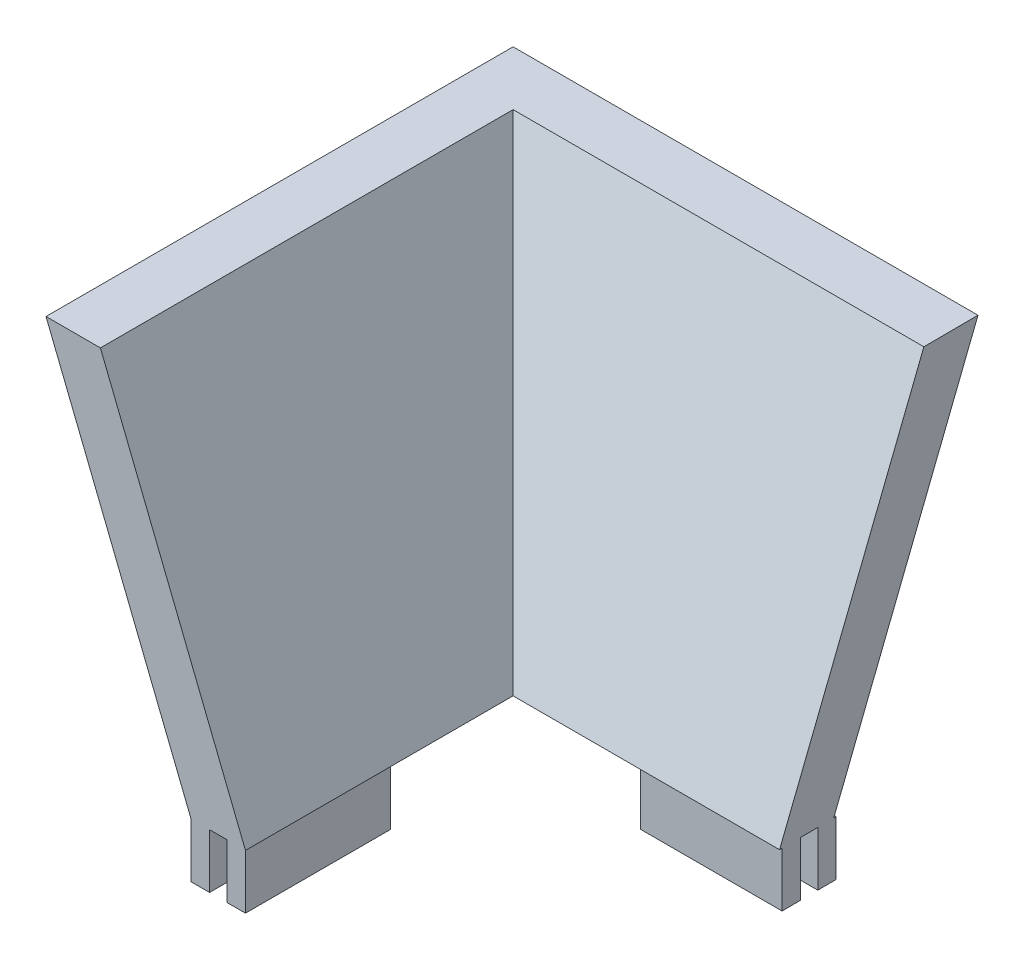
SolidWorks part; units mm, degrees
ref_plane "Front Plane" through (0, 0, 0) normal (0, 0, 1) x (1, 0, 0)
ref_plane "Top Plane" through (0, 0, 0) normal (0, 1, 0) x (1, 0, 0)
ref_plane "Right Plane" through (0, 0, 0) normal (1, 0, 0) x (0, 0, -1)
sketch "Sketch1" plane through (0, 0, 0) normal (0, 1, 0) x (1, 0, 0)
  line L1 (0, 0) -> (227.33, 0)
  line L2 (0, 0) -> (0, 225.552)
  line L3 (0, 225.552) -> (227.33, 225.552)
  line L4 (227.33, 0) -> (227.33, 225.552)
  dimension "D1" = 227.33
  dimension "D2" = 225.552
ref_plane "Plane1" through (0, 127, 0) normal (0, 1, 0) x (1, 0, 0)
sketch "Sketch2" plane through (0, 127, 0) normal (0, 1, 0) x (1, 0, 0)
  line L8 (-50.8, -50.8) -> (278.13, -50.8)
  line L9 (278.13, -50.8) -> (278.13, 276.352)
  line L10 (278.13, 276.352) -> (-50.8, 276.352)
  line L11 (-50.8, 276.352) -> (-50.8, -50.8)
  line L12 (-50.8, -50.8) -> (278.13, -50.8)
  line L13 (278.13, -50.8) -> (278.13, 276.352)
  line L14 (278.13, 276.352) -> (-50.8, 276.352)
  line L15 (-50.8, 276.352) -> (-50.8, -50.8)
  dimension "D1" = 50.8
loft "Loft1" add profiles "Sketch2" section "Sketch2" section "Sketch1"
sketch "Sketch3" plane through (0, 127, 0) normal (0, 1, 0) x (1, 0, 0)
  line L8 (-31.75, 257.302) -> (-31.75, -31.75)
  line L9 (-31.75, -31.75) -> (259.08, -31.75)
  line L10 (259.08, -31.75) -> (259.08, 257.302)
  line L11 (259.08, 257.302) -> (-31.75, 257.302)
  line L12 (-31.75, 257.302) -> (-31.75, -31.75)
  line L13 (-31.75, -31.75) -> (259.08, -31.75)
  line L14 (259.08, -31.75) -> (259.08, 257.302)
  line L15 (259.08, 257.302) -> (-31.75, 257.302)
  dimension "D1" = 19.05
sketch "Sketch4" plane through (0, 0, 0) normal (0, -1, 0) x (1, 0, 0)
  line L8 (208.28, -19.05) -> (19.05, -19.05)
  line L9 (19.05, -19.05) -> (19.05, -206.502)
  line L10 (19.05, -206.502) -> (208.28, -206.502)
  line L11 (208.28, -206.502) -> (208.28, -19.05)
  line L12 (208.28, -19.05) -> (19.05, -19.05)
  line L13 (19.05, -19.05) -> (19.05, -206.502)
  line L14 (19.05, -206.502) -> (208.28, -206.502)
  line L15 (208.28, -206.502) -> (208.28, -19.05)
  dimension "D1" = 19.05
loft "Cut-Loft3" cut profiles "Sketch3" section "Sketch4" section "Sketch3"
sketch "Sketch5" plane through (0, 0, 0) normal (0, -1, 0) x (1, 0, 0)
  line L0 (0, -61.976) -> (6.477, -61.976)
  line L5 (0, -61.976) -> (0, -163.576)
  line L6 (0, 0) -> (0, -225.552) construction
  line L7 (6.477, -61.976) -> (6.477, -163.576)
  line L8 (6.477, -163.576) -> (0, -163.576)
  line L9 (19.05, -61.976) -> (19.05, -163.576)
  line L10 (19.05, -19.05) -> (19.05, -206.502) construction
  line L11 (19.05, -61.976) -> (12.573, -61.976)
  line L12 (12.573, -61.976) -> (12.573, -163.576)
  line L13 (12.573, -163.576) -> (19.05, -163.576)
  line L14 (19.05, -19.05) -> (208.28, -206.502) construction
  line L15 (164.465, -5.588) -> (62.865, -5.588)
  line L16 (164.465, 0.889) -> (62.865, 0.889)
  line L17 (164.465, 0.889) -> (164.465, -5.588)
  line L18 (62.865, -5.588) -> (62.865, 0.889)
  line L19 (164.465, -11.684) -> (62.865, -11.684)
  line L20 (164.465, -18.161) -> (62.865, -18.161)
  line L21 (164.465, -18.161) -> (164.465, -11.684)
  line L22 (62.865, -11.684) -> (62.865, -18.161)
  line L23 (220.853, -163.576) -> (220.853, -61.976)
  line L24 (227.33, -163.576) -> (227.33, -61.976)
  line L25 (227.33, -163.576) -> (220.853, -163.576)
  line L26 (220.853, -61.976) -> (227.33, -61.976)
  line L27 (214.757, -163.576) -> (214.757, -61.976)
  line L28 (208.28, -163.576) -> (208.28, -61.976)
  line L29 (208.28, -163.576) -> (214.757, -163.576)
  line L30 (214.757, -61.976) -> (208.28, -61.976)
  line L31 (62.865, -219.964) -> (164.465, -219.964)
  line L32 (62.865, -226.441) -> (164.465, -226.441)
  line L33 (62.865, -226.441) -> (62.865, -219.964)
  line L34 (164.465, -219.964) -> (164.465, -226.441)
  line L35 (62.865, -213.868) -> (164.465, -213.868)
  line L36 (62.865, -207.391) -> (164.465, -207.391)
  line L37 (62.865, -207.391) -> (62.865, -213.868)
  line L38 (164.465, -213.868) -> (164.465, -207.391)
  point P5 (0, -112.776)
  point P12 (19.05, -112.776)
  point P14 (113.665, -112.776)
  point P46 (113.665, -112.776)
  dimension "D1" = 101.6
  dimension "D2" = 6.096
  dimension "D3" = 4
extrude "Boss-Extrude1" add sketch "Sketch5" along normal blind 19.05
sketch "Sketch6" plane through (0, 0, 0) normal (0, 1, 0) x (1, 0, 0)
  line L0 (112.0125, 276.352) -> (113.665, -50.8)
  line L1 (278.13, 276.352) -> (-50.8, 276.352) construction
  line L2 (-50.8, -50.8) -> (278.13, -50.8) construction
  line L3 (-50.8, 112.776) -> (278.13, 112.776)
  line L4 (-50.8, 276.352) -> (-50.8, -50.8) construction
  line L5 (278.13, -50.8) -> (278.13, 276.352) construction
  line L6 (112.0125, 276.352) -> (278.13, 276.352)
  line L7 (278.13, 276.352) -> (278.13, -50.8)
  line L8 (278.13, -50.8) -> (-50.8, -50.8)
  line L9 (-50.8, -50.8) -> (-50.8, 112.776)
extrude "Cut-Extrude2" cut sketch "Sketch6" against normal blind 164.846 and the other way blind 251.206 contours L7 L6 L0 L3 | L8 L7 L3 L0 | L9 L8 L0 L3
